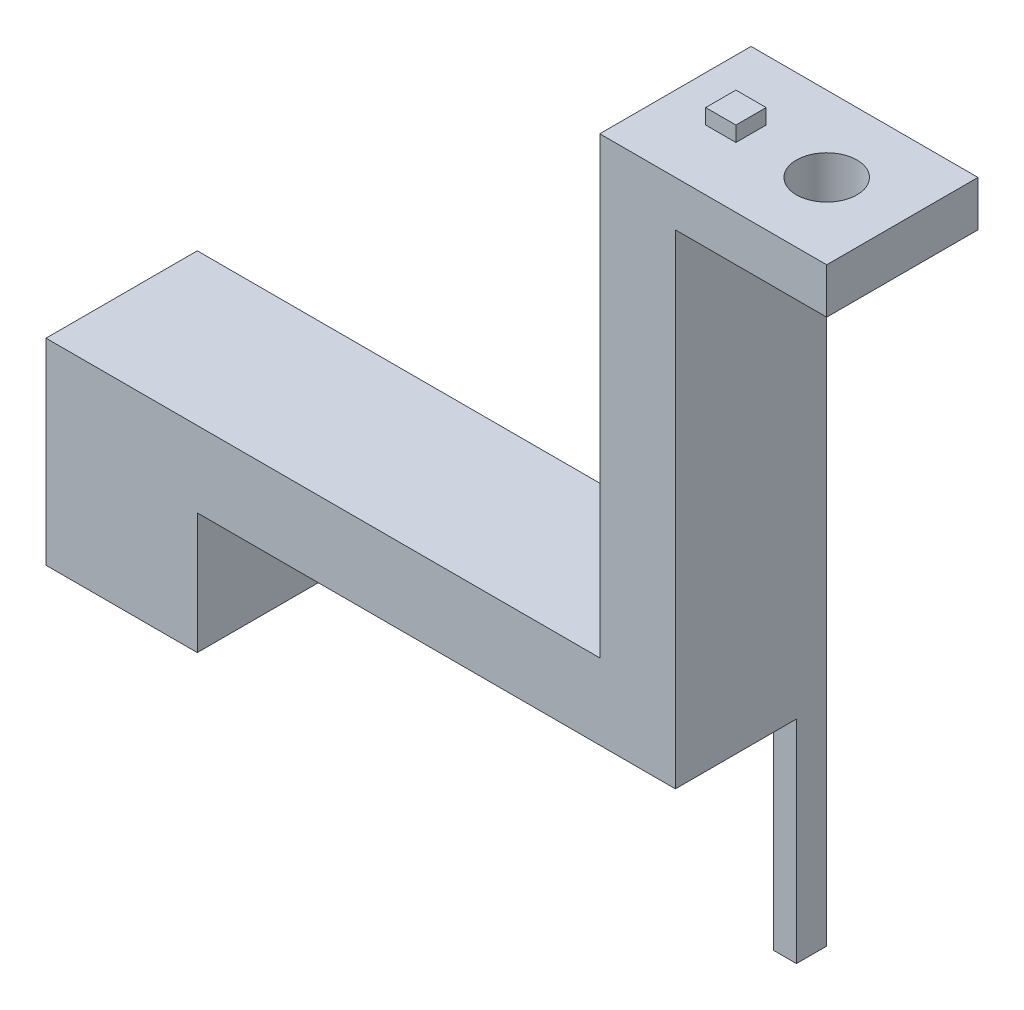
SolidWorks part; units mm, degrees
ref_plane "Front Plane" through (0, 0, 0) normal (0, 0, 1) x (1, 0, 0)
ref_plane "Top Plane" through (0, 0, 0) normal (0, 1, 0) x (1, 0, 0)
ref_plane "Right Plane" through (0, 0, 0) normal (1, 0, 0) x (0, 0, -1)
sketch "Sketch1" plane through (0, 0, 0) normal (0, 0, 1) x (1, 0, 0)
  line L0 (0, 8.6428) -> (0, -8.815) construction
  line L1 (-7.8399, 0) -> (7.1786, 0) construction
  line L2 (36.6, -2.7124) -> (36.6, 24.7717) construction
  line L3 (-5.2779, 43) -> (40.9314, 43) construction
  line L4 (10, 13) -> (36.6, 13)
  line L5 (0, 13) -> (10, 13)
  line L6 (0, 13) -> (0, 0)
  line L7 (0, 0) -> (10, 0)
  line L8 (10, 8) -> (10, 0)
  line L9 (36.6, 13) -> (36.6, 43)
  line L11 (41.6, 40) -> (41.6, 8)
  line L12 (41.6, 8) -> (10, 8)
  line L13 (41.6, 40) -> (51.6, 40)
  line L14 (51.6, 40) -> (51.6, 43)
  line L16 (36.6, 43) -> (51.6, 43)
  dimension "D4" = 30
  dimension "D1" = 36.6
  dimension "D2" = 10
  dimension "D3" = 13
  dimension "D5" = 15
  dimension "D6" = 5
  dimension "D7" = 5
  dimension "D8" = 3
  dimension "D9" = 8
  dimension "D10" = 31.6
extrude "Boss-Extrude1" add sketch "Sketch1" along normal blind 10
sketch "Sketch2" plane through (0, 0, 0) normal (0, -1, 0) x (1, 0, 0)
  line L0 (5, 15.6268) -> (5, -4.9051) construction
  line L1 (2.45, 6.55) -> (7.55, 6.55)
  line L2 (2.45, 6.55) -> (2.45, 3.45)
  line L3 (2.45, 3.45) -> (7.55, 3.45)
  line L4 (7.55, 6.55) -> (7.55, 3.45)
  line L5 (-4.1598, 5) -> (14.1324, 5) construction
  line L11 (0, 0) -> (10, 0) construction
  line L12 (0, 10) -> (0, 0) construction
  dimension "D1" = 5
  dimension "D2" = 5
  dimension "D3" = 5.1
  dimension "D4" = 3.1
extrude "Cut-Extrude1" cut sketch "Sketch2" against normal blind 10 contours L2 L1 L4 L3
sketch "Sketch3" plane through (0, 43, 0) normal (0, 1, 0) x (1, 0, 0)
  line L0 (29.4648, -5) -> (60.8247, -5) construction
  line L3 (51.6, 0) -> (36.6, 0) construction
  line L4 (51.6, -10) -> (51.6, 0) construction
  line L6 (39.6, -6) -> (41.6, -6)
  line L7 (39.6, -6) -> (39.6, -4)
  line L8 (39.6, -4) -> (41.6, -4)
  line L9 (41.6, -6) -> (41.6, -4)
  circle A0 centre (46.6, -5) radius 2
  dimension "D2" = 4
  dimension "D3" = 3
  dimension "D1" = 5
  dimension "D4" = 2
  dimension "D5" = 2
  dimension "D6" = 3
extrude "Boss-Extrude2" add sketch "Sketch3" along normal blind 1 contours L7 L6 L9 L8
sketch "Sketch11" plane through (0, 43, 0) normal (0, 1, 0) x (1, 0, 0)
  line L0 (29.4648, -5) -> (60.8247, -5) construction
  line L2 (51.6, -10) -> (51.6, 0) construction
  line L5 (39.6, -6) -> (41.6, -6) construction
  line L6 (39.6, -6) -> (41.6, -6)
  line L7 (39.6, -6) -> (39.6, -4)
  line L8 (39.6, -4) -> (41.6, -4)
  line L9 (41.6, -6) -> (41.6, -4)
  circle A0 centre (46.6, -5) radius 2
  dimension "D2" = 4
  dimension "D3" = 0
  dimension "D1" = 3
  dimension "D4" = 2
  dimension "D5" = 2
  dimension "D6" = 3
extrude "Cut-Extrude4" cut sketch "Sketch11" against normal up to next contours A0
sketch "Sketch12" plane through (0, 8, 0) normal (0, -1, 0) x (1, 0, 0)
  line L0 (10, 0) -> (41.6, 0) construction
  line L1 (41.6, 2) -> (40.1, 2)
  line L2 (41.6, 2) -> (41.6, 0)
  line L3 (41.6, 0) -> (40.1, 0)
  line L4 (40.1, 2) -> (40.1, 0)
  line L5 (41.6, 10) -> (41.6, 0) construction
  line L6 (60.8694, 4.3561) -> (126.3325, 4.3561)
  dimension "D1" = 1.5
  dimension "D2" = 2
extrude "Boss-Extrude4" add sketch "Sketch12" along normal blind 14 contours L1 L4 L0 L5
